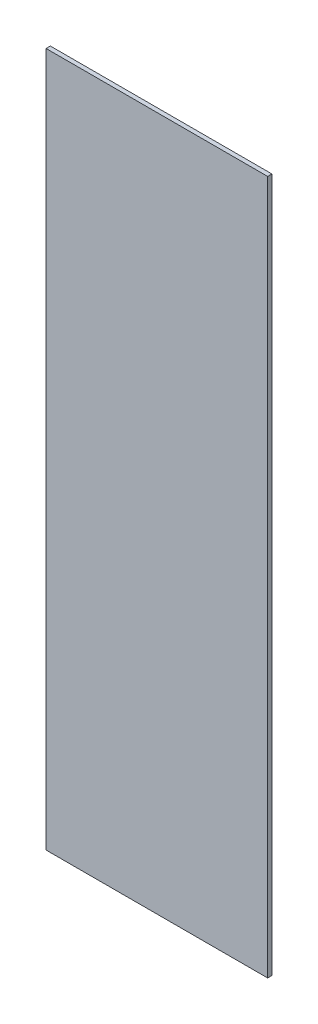
SolidWorks part; units mm, degrees
ref_plane "Front Plane" through (0, 0, 0) normal (0, 0, 1) x (1, 0, 0)
ref_plane "Top Plane" through (0, 0, 0) normal (0, 1, 0) x (1, 0, 0)
ref_plane "Right Plane" through (0, 0, 0) normal (1, 0, 0) x (0, 0, -1)
sketch "Sketch1" plane through (0, 0, 0) normal (0, 0, 1) x (1, 0, 0)
  line L0 (-41.5, -50) -> (-41.5, -110)
  line L1 (-41.5, -50) -> (41.5, -50) construction
  line L2 (-41.5, -50) -> (-41.5, 50)
  line L3 (-41.5, 50) -> (41.5, 50) construction
  line L4 (41.5, -50) -> (41.5, 50)
  line L5 (-41.5, -50) -> (41.5, 50) construction
  line L6 (-41.5, 50) -> (41.5, -50) construction
  line L7 (41.5, -50) -> (41.5, -110)
  line L8 (41.5, -110) -> (-41.5, -110)
  line L10 (-41.5, 50) -> (41.5, 50) construction
  line L11 (-41.5, 50) -> (-41.5, 150)
  line L12 (-41.5, 150) -> (41.5, 150)
  line L13 (41.5, 50) -> (41.5, 150)
  point P0 (0, 0)
extrude "Boss-Extrude1" add sketch "Sketch1" along normal blind 1.6
